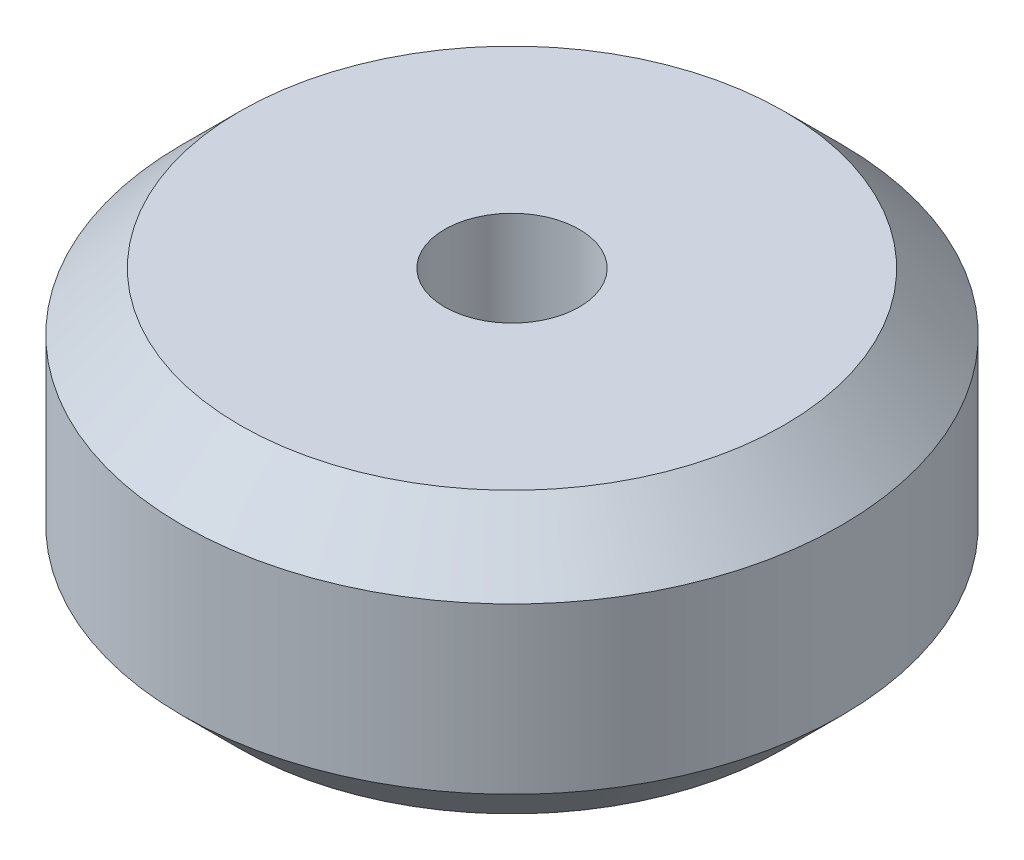
SolidWorks part; units mm, degrees
ref_plane "前视基准面" through (0, 0, 0) normal (0, 0, 1) x (1, 0, 0)
ref_plane "上视基准面" through (0, 0, 0) normal (0, 1, 0) x (1, 0, 0)
ref_plane "右视基准面" through (0, 0, 0) normal (1, 0, 0) x (0, 0, -1)
other "Configuration Table"
sketch "草图1" plane through (0, 0, 0) normal (0, 1, 0) x (1, 0, 0)
  circle A0 centre (0, 0) radius 12
  dimension "D1" = 24
extrude "凸台-拉伸1" add sketch "草图1" along normal mid plane 10.2
chamfer "倒角1" distance 2.1 angle 45 2 edges at (0, -5.1, 12) (0, 5.1, 12)
sketch "草图2" plane through (0, 0, 0) normal (0, 1, 0) x (1, 0, 0)
  circle A0 centre (0, 0) radius 2.45
  dimension "D1" = 4.9
extrude "切除-拉伸1" cut sketch "草图2" against normal through all both and the other way through all
